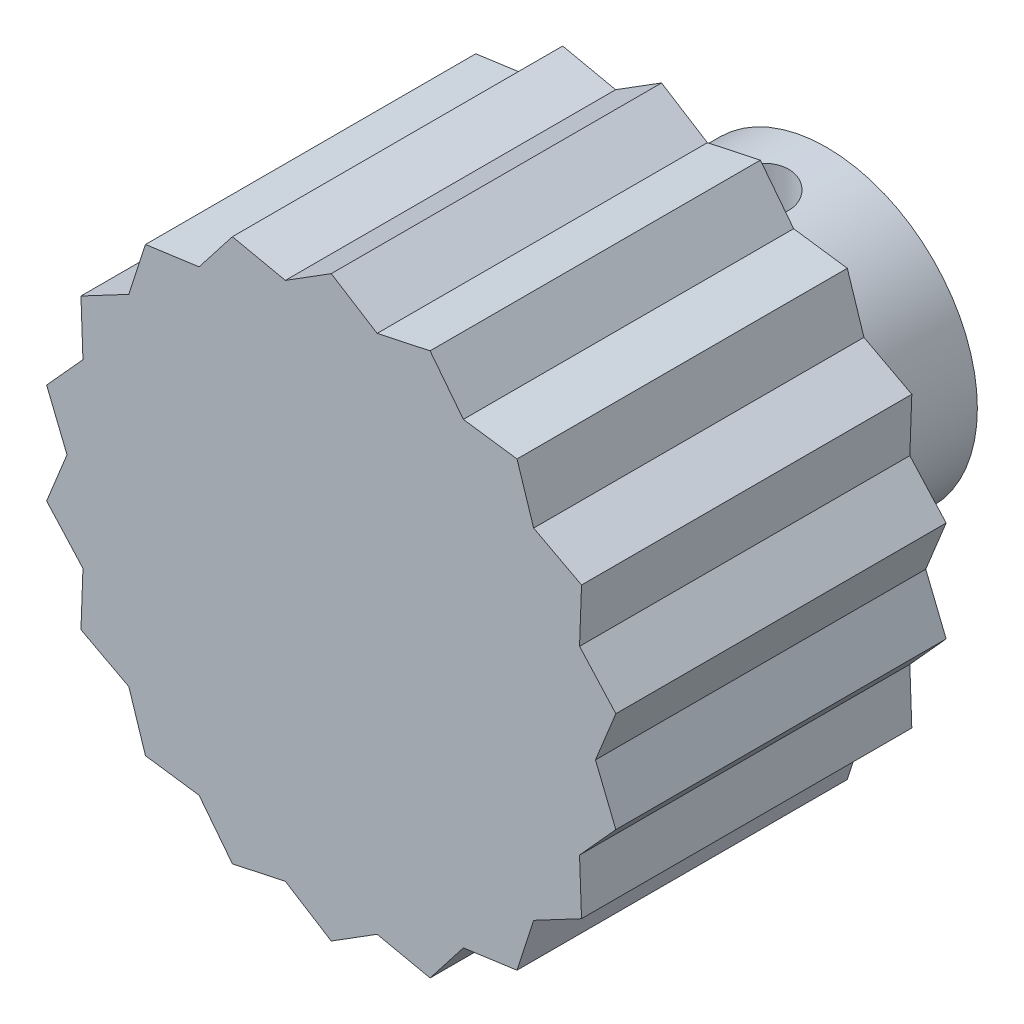
SolidWorks part; units mm, degrees
ref_plane "Alzado" through (0, 0, 0) normal (0, 0, 1) x (1, 0, 0)
ref_plane "Planta" through (0, 0, 0) normal (0, 1, 0) x (1, 0, 0)
ref_plane "Vista lateral" through (0, 0, 0) normal (1, 0, 0) x (0, 0, -1)
sketch "Croquis1" plane through (0, 0, 0) normal (0, 0, 1) x (1, 0, 0)
  circle A0 centre (0, 0) radius 17.5
  dimension "D1" = 35
extrude "Saliente-Extruir1" add sketch "Croquis1" along normal blind 20
sketch "Croquis2" plane through (0, 0, 0) normal (0, 0, -1) x (-1, 0, 0)
  circle A0 centre (0, 0) radius 9.125
  circle A1 centre (0, 0) radius 4.125
  dimension "D1" = 8.25
  dimension "D2" = 5
extrude "Saliente-Extruir2" add sketch "Croquis2" along normal blind 10
sketch "Croquis3" plane through (0, 0, 20) normal (0, 0, 1) x (1, 0, 0)
  line L0 (0, 17.5) -> (0, 0) construction
  line L1 (2.7784, 15.7569) -> (0, 0) construction
  line L2 (0, 17.5) -> (2.7784, 15.7569)
  line L3 (2.7784, 15.7569) -> (5.9854, 16.4446)
  line L4 (8, 13.8564) -> (11.2488, 13.4058)
  line L5 (5.9854, 16.4446) -> (8, 13.8564)
  line L6 (12.2567, 10.2846) -> (15.1554, 8.75)
  line L7 (11.2488, 13.4058) -> (12.2567, 10.2846)
  line L8 (15.0351, 5.4723) -> (17.2341, 3.0388)
  line L9 (15.1554, 8.75) -> (15.0351, 5.4723)
  line L10 (16, 0) -> (17.2341, -3.0388)
  line L11 (17.2341, 3.0388) -> (16, 0)
  line L12 (15.0351, -5.4723) -> (15.1554, -8.75)
  line L13 (17.2341, -3.0388) -> (15.0351, -5.4723)
  line L14 (12.2567, -10.2846) -> (11.2488, -13.4058)
  line L15 (15.1554, -8.75) -> (12.2567, -10.2846)
  line L16 (8, -13.8564) -> (5.9854, -16.4446)
  line L17 (11.2488, -13.4058) -> (8, -13.8564)
  line L18 (2.7784, -15.7569) -> (0, -17.5)
  line L19 (5.9854, -16.4446) -> (2.7784, -15.7569)
  line L20 (-2.7784, -15.7569) -> (-5.9854, -16.4446)
  line L21 (0, -17.5) -> (-2.7784, -15.7569)
  line L22 (-8, -13.8564) -> (-11.2488, -13.4058)
  line L23 (-5.9854, -16.4446) -> (-8, -13.8564)
  line L24 (-12.2567, -10.2846) -> (-15.1554, -8.75)
  line L25 (-11.2488, -13.4058) -> (-12.2567, -10.2846)
  line L26 (-15.0351, -5.4723) -> (-17.2341, -3.0388)
  line L27 (-15.1554, -8.75) -> (-15.0351, -5.4723)
  line L28 (-16, 0) -> (-17.2341, 3.0388)
  line L29 (-17.2341, -3.0388) -> (-16, 0)
  line L30 (-15.0351, 5.4723) -> (-15.1554, 8.75)
  line L31 (-17.2341, 3.0388) -> (-15.0351, 5.4723)
  line L32 (-12.2567, 10.2846) -> (-11.2488, 13.4058)
  line L33 (-15.1554, 8.75) -> (-12.2567, 10.2846)
  line L34 (-8, 13.8564) -> (-5.9854, 16.4446)
  line L35 (-11.2488, 13.4058) -> (-8, 13.8564)
  line L36 (-2.7784, 15.7569) -> (0, 17.5)
  line L37 (-5.9854, 16.4446) -> (-2.7784, 15.7569)
  circle A0 centre (0, 0) radius 17.5 construction
  circle A2 centre (0, 0) radius 19
  point P62 (0, 0)
  dimension "D4" = 38
  dimension "D1" = 10
  dimension "D2" = 16
  dimension "D3" = 18
extrude "Cortar-Extruir1" cut sketch "Croquis3" against normal up to next
sketch "Croquis4" plane through (0, 0, 0) normal (0, 1, 0) x (1, 0, 0)
  line L0 (0, 0) -> (0, 10) construction
  line L1 (9.125, 10) -> (-9.125, 10) construction
  circle A1 centre (0, 5.75) radius 1.95
  dimension "D2" = 3.9
  dimension "D1" = 4.25
extrude "Cortar-Extruir2" cut sketch "Croquis4" against normal through all both and the other way through all
sketch "Croquis5" plane through (0, 0, 0) normal (0, 0, -1) x (-1, 0, 0)
  circle A1 centre (0, 0) radius 4.125
  circle A2 centre (0, 0) radius 4.125
  dimension "D1" = 0
extrude "Cortar-Extruir3" cut sketch "Croquis5" against normal blind 5
